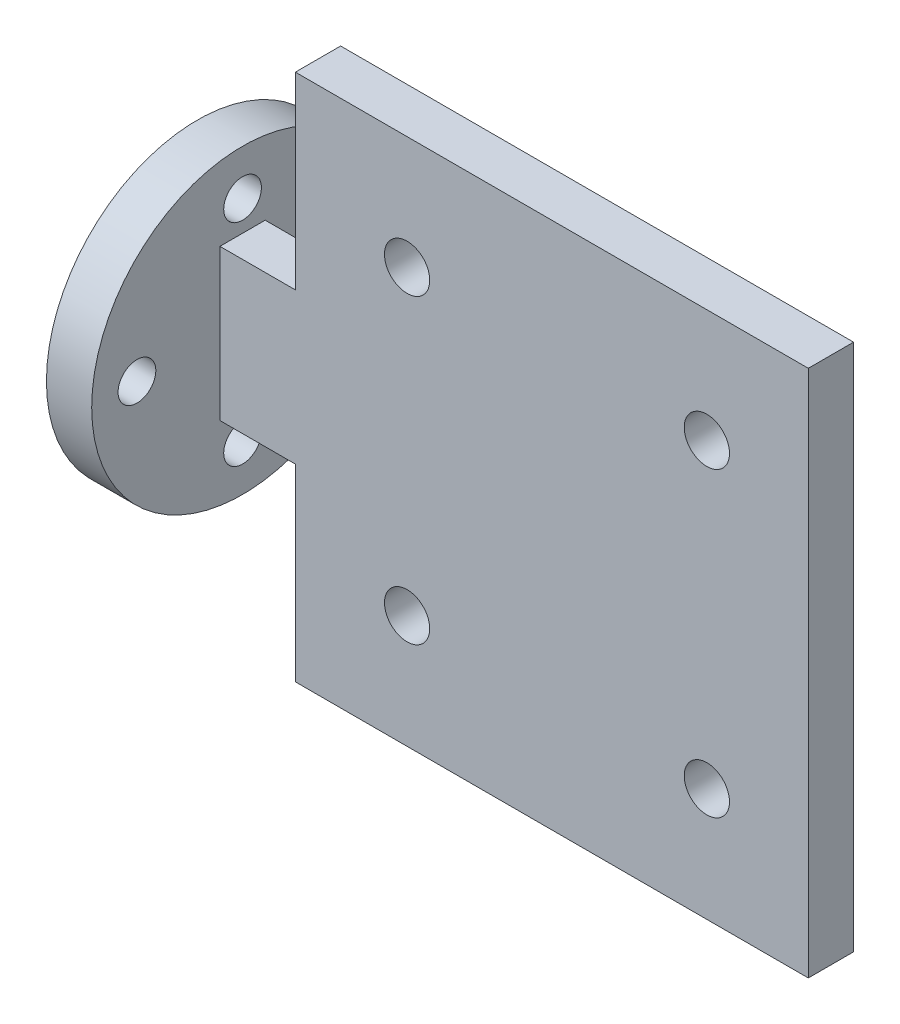
SolidWorks part; units mm, degrees
ref_plane "前视基准面" through (0, 0, 0) normal (0, 0, 1) x (1, 0, 0)
ref_plane "上视基准面" through (0, 0, 0) normal (0, 1, 0) x (1, 0, 0)
ref_plane "右视基准面" through (0, 0, 0) normal (1, 0, 0) x (0, 0, -1)
sketch "草图1" plane through (0, 0, 0) normal (0, 0, 1) x (1, 0, 0)
  line L1 (17, -17.5) -> (-17, -17.5)
  line L2 (17, -17.5) -> (17, 17.5)
  line L3 (17, 17.5) -> (-17, 17.5)
  line L4 (-17, -17.5) -> (-17, 17.5)
  line L5 (17, -17.5) -> (-17, 17.5) construction
  line L6 (17, 17.5) -> (-17, -17.5) construction
  point P0 (0, 0)
  dimension "D1" = 35
  dimension "D2" = 34
extrude "凸台-拉伸1" add sketch "草图1" along normal blind 3
sketch "草图2" plane through (0, 0, 3) normal (0, 0, 1) x (1, 0, 0)
  line L0 (-17, 0) -> (-28.5683, 0) construction
  line L1 (-17, 17.5) -> (-17, -17.5) construction
  line L2 (-17, -5) -> (-22, -5)
  line L3 (-17, 0) -> (-22, 0)
  line L4 (-17, -5) -> (-17, 5)
  line L5 (-17, 5) -> (-22, 5)
  line L6 (-22, -5) -> (-22, 5)
  line M3 (-17, 17.5) -> (-17, -17.5)
  dimension "D1" = 5
  dimension "D2" = 5
extrude "凸台-拉伸2" add sketch "草图2" against normal blind 3 contours L6 L3 L5 M3 | L6 L2 L3 M3
sketch "草图3" plane through (-22, 0, 0) normal (-1, 0, 0) x (0, 0, 1)
  line L0 (1.5, 5) -> (1.5, -5) construction
  line L1 (0, 5) -> (3, 5) construction
  line L2 (0, -5) -> (3, -5) construction
  line L3 (0, 0) -> (3, 0) construction
  line L4 (0, -5) -> (0, 5) construction
  line L5 (3, -5) -> (3, 5) construction
  circle A0 centre (1.5, 0) radius 10
  dimension "D1" = 20
extrude "凸台-拉伸3" add sketch "草图3" along normal blind 3
sketch "草图4" plane through (-25, 0, 0) normal (-1, 0, 0) x (0, 0, 1)
  circle A0 centre (1.5, 0) radius 7 construction
  circle A1 centre (1.5, 7) radius 1.25
  circle A2 centre (8.5, 0) radius 1.25
  circle A3 centre (1.5, -7) radius 1.25
  circle A4 centre (-5.5, 0) radius 1.25
  point P14 (1.5, 0)
  dimension "D1" = 2.5
  dimension "D2" = 14
  dimension "D3" = 4
extrude "切除-拉伸1" cut sketch "草图4" against normal blind 3
sketch "草图5" plane through (-25, 0, 0) normal (-1, 0, 0) x (0, 0, 1)
  circle A1 centre (1.5, 0) radius 1.75
  dimension "D1" = 3.5
sketch "草图6" plane through (-25, 0, 0) normal (-1, 0, 0) x (0, 0, 1)
  circle A0 centre (1.5, 0) radius 1.75 construction
  circle A1 centre (1.5, 0) radius 1.75
extrude "切除-拉伸6" cut sketch "草图6" against normal blind 1.5
sketch "草图7" plane through (0, 0, 3) normal (0, 0, 1) x (1, 0, 0)
  circle A0 centre (10.2752, 10) radius 1.5
  circle A1 centre (10.2752, -10) radius 1.5
  circle A2 centre (-9.5936, 10) radius 1.5
  circle A3 centre (-9.5936, -10) radius 1.5
  dimension "D1" = 10
  dimension "D2" = 10
  dimension "D3" = 10
  dimension "D5" = 3
  dimension "D4" = 10
extrude "切除-拉伸7" cut sketch "草图7" against normal blind 3
